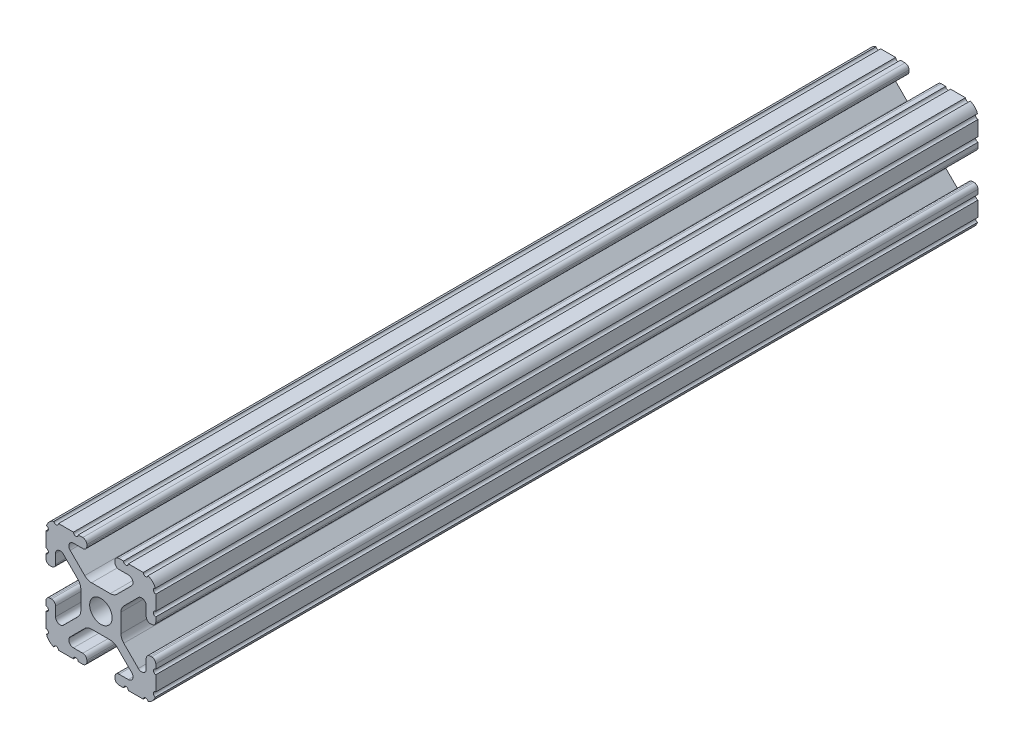
SolidWorks part; units mm, degrees
ref_plane "Front Plane" through (0, 0, 0) normal (0, 0, 1) x (1, 0, 0)
ref_plane "Top Plane" through (0, 0, 0) normal (0, 1, 0) x (1, 0, 0)
ref_plane "Right Plane" through (0, 0, 0) normal (1, 0, 0) x (0, 0, -1)
sketch "Sketch2" plane through (0, 0, 0) normal (0, 0, 1) x (1, 0, 0)
  line L0 (0, 12.7) -> (0, -12.7) construction
  line L1 (-12.7, 0) -> (12.7, 0) construction
  line L2 (3.2512, -12.7) -> (12.7, -12.7)
  line L3 (12.7, -12.7) -> (12.7, -3.2512)
  line L4 (3.2512, -12.7) -> (3.2512, -10.4902)
  line L5 (3.2512, -10.4902) -> (8.9276, -10.4902)
  line L6 (8.9276, -10.4902) -> (3.0856, -4.6482)
  line L7 (0, 0) -> (12.7, -12.7) construction
  line L8 (12.7, -3.2512) -> (10.4902, -3.2512)
  line L9 (10.4902, -3.2512) -> (10.4902, -8.9276)
  line L10 (10.4902, -8.9276) -> (4.6482, -3.0856)
  circle A0 centre (0, 0) radius 2.6035
  arc A1 (6.3485, -10.4902) -> (7.1039, -8.6665) centre (6.3485, -9.4219) ccw construction
  point P8 (0, -4.6482)
  dimension "Center Hole Diameter" = 5.207
  dimension "Rail Height" = 25.4
  dimension "Rail Width" = 25.4
  dimension "T-Slot Width" = 6.5024
  dimension "Slot Inner Width" = 14.8336
  dimension "Thickness" = 2.2098
  dimension "Slot Depth" = 5.842
  dimension "D1" = 2.2098
sketch "Sketch3" plane through (0, 0, 0) normal (1, 0, 0) x (0, 0, -1)
  line L0 (-95.123, -12.7) -> (95.123, -12.7) construction
  line L1 (-69.723, 0) -> (69.723, 0) construction
  line L2 (95.123, 0) -> (-95.123, 0) construction
sketch "Sketch4" plane through (0, 0, 0) normal (0, 0, 1) x (1, 0, 0)
  line L0 (4.1904, -12.7) -> (10.1173, -12.7)
  line L1 (3.2512, -12.7) -> (12.7, -12.7) construction
  line L2 (3.2512, -12.7) -> (3.2512, -10.4902) construction
  line L3 (3.2512, -10.4902) -> (8.9276, -10.4902) construction
  line L4 (3.2512, -11.4294) -> (3.2512, -11.7608)
  line L5 (4.1904, -10.4902) -> (6.3485, -10.4902)
  line L6 (0, -4.6482) -> (2.164, -4.6482)
  line L7 (8.9276, -10.4902) -> (3.0856, -4.6482) construction
  line L8 (3.7373, -5.2999) -> (7.1039, -8.6665)
  line L9 (12.7, -12.7) -> (12.7, -3.2512) construction
  line L10 (10.4902, -8.9276) -> (4.6482, -3.0856) construction
  line L11 (10.4902, -3.2512) -> (10.4902, -8.9276) construction
  line L12 (10.4902, -6.3485) -> (10.4902, -4.1904)
  line L13 (12.7, -3.2512) -> (10.4902, -3.2512) construction
  line L14 (11.4294, -3.2512) -> (11.7608, -3.2512)
  line L15 (12.7, -4.1904) -> (12.7, -10.1173)
  line L16 (8.6665, -7.1039) -> (5.2999, -3.7373)
  line L17 (4.6482, 0) -> (4.6482, -2.164)
  line L18 (-12.7, 0) -> (12.7, 0) construction
  line L19 (0, -4.6482) -> (0, -2.6035)
  line L20 (0, 12.7) -> (0, -12.7) construction
  line L21 (4.6482, 0) -> (2.6035, 0)
  arc A0 (3.2512, -11.7608) -> (4.1904, -12.7) centre (4.1904, -11.7608) ccw
  arc A2 (3.2512, -11.4294) -> (4.1904, -10.4902) centre (4.1904, -11.4294) cw
  arc A3 (6.3485, -10.4902) -> (7.1039, -8.6665) centre (6.3485, -9.4219) ccw
  arc A4 (2.164, -4.6482) -> (3.7373, -5.2999) centre (2.164, -6.8732) cw
  arc A5 (10.1173, -12.7) -> (12.7, -10.1173) centre (10.1173, -10.1173) ccw
  arc A6 (8.6665, -7.1039) -> (10.4902, -6.3485) centre (9.4219, -6.3485) ccw
  arc A7 (10.4902, -4.1904) -> (11.4294, -3.2512) centre (11.4294, -4.1904) cw
  arc A8 (11.7608, -3.2512) -> (12.7, -4.1904) centre (11.7608, -4.1904) cw
  arc A9 (5.2999, -3.7373) -> (4.6482, -2.164) centre (6.8732, -2.164) cw
  circle A10 centre (0, 0) radius 2.6035 construction
  arc A11 (0, -2.6035) -> (2.6035, 0) centre (0, 0) ccw
  dimension "D1" = 2.5827
  dimension "D2" = 2.225
  dimension "D3" = 0.9392
extrude "Boss-Extrude1" add sketch "Sketch4" along normal up to vertex (95.123 mm away) from vertex at -95.123 starting at point (0, -12.7, -95.123)
sketch "Sketch5" plane through (0, 0, 0) normal (0, 0, 1) x (1, 0, 0)
  line L0 (3.2512, -12.7) -> (12.7, -12.7) construction
  line L1 (4.1904, -10.4902) -> (6.3485, -10.4902) construction
  line L3 (0, 0) -> (12.7, -12.7) construction
  line L4 (6.3485, -10.4902) -> (6.3485, -12.7) construction
  line L5 (8.9276, -10.4902) -> (3.0856, -4.6482) construction
  circle A0 centre (10.3562, -12.7) radius 0.5524
  circle A1 centre (5.796, -12.7) radius 0.5524
  circle A2 centre (12.7, -10.3562) radius 0.5524
  circle A3 centre (12.7, -5.796) radius 0.5524
  point P10 (5.2694, -10.4902)
  point P12 (9.4219, -6.3485)
  dimension "D1" = 1.1049
extrude "Cut-Extrude1" cut sketch "Sketch5" against normal through all both and the other way through all
mirror "Mirror1" about plane through (0, 0, 0) normal (1, 0, 0) of bodies 137 134
mirror "Mirror2" about plane through (0, 0, 0) normal (0, 1, 0) of bodies 135
equation "\"D1@Sketch2\"=\"Thickness@Sketch2\""
equation "\"D2@Sketch4\"=\"Slot Inner Width@Sketch2\"*0.15"
equation "\"D1@Sketch4\"=\"D3@Sketch4\"*2.75"
equation "\"D3@Sketch4\"=\"Thickness@Sketch2\"*0.425"
equation "\"D1@Sketch5\"=\"Thickness@Sketch2\"*0.5"
equation "\"D1@Boss-Extrude1\"=\"Length@Sketch3\""
